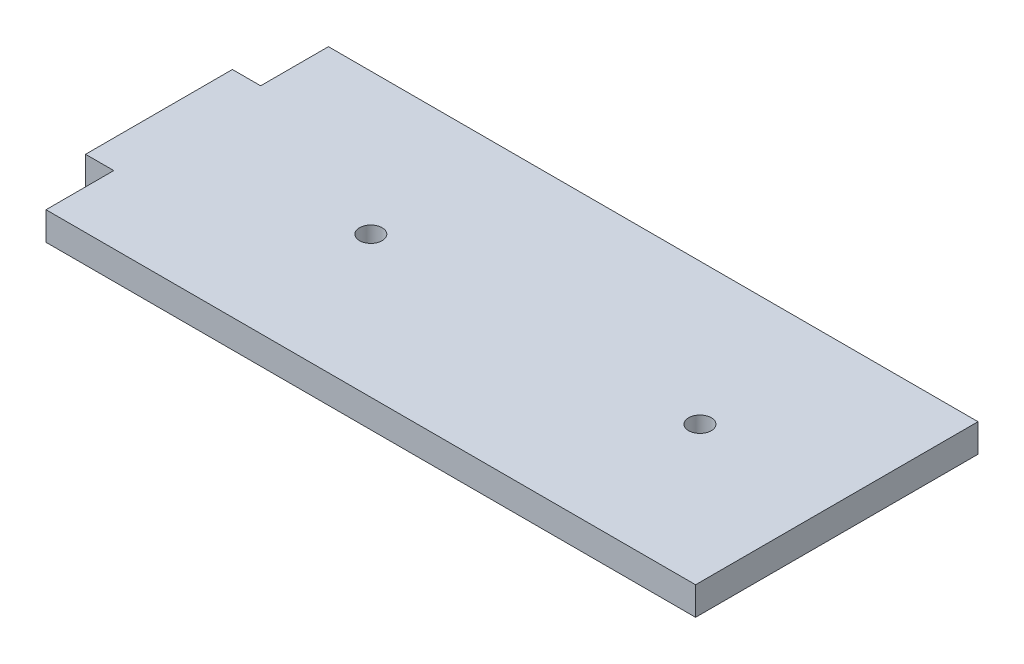
SolidWorks part; units mm, degrees
ref_plane "Front Plane" through (0, 0, 0) normal (0, 0, 1) x (1, 0, 0)
ref_plane "Top Plane" through (0, 0, 0) normal (0, 1, 0) x (1, 0, 0)
ref_plane "Right Plane" through (0, 0, 0) normal (1, 0, 0) x (0, 0, -1)
sketch "Sketch1" plane through (0, 0, 0) normal (0, 1, 0) x (1, 0, 0)
  line L1 (-38.1, 15.875) -> (38.1, 15.875)
  line L2 (-38.1, 15.875) -> (-38.1, -15.875)
  line L3 (-38.1, -15.875) -> (38.1, -15.875)
  line L4 (38.1, 15.875) -> (38.1, -15.875)
  line L5 (-38.1, 15.875) -> (38.1, -15.875) construction
  line L6 (-38.1, -15.875) -> (38.1, 15.875) construction
  point P0 (0, 0)
  dimension "D1" = 31.75
  dimension "D2" = 76.2
extrude "Boss-Extrude1" add sketch "Sketch1" along normal blind 3.175
sketch "Sketch2" plane through (0, 3.175, 0) normal (0, 1, 0) x (1, 0, 0)
  line L0 (-38.1, 15.875) -> (-38.1, -15.875) construction
  line L5 (38.1, 15.875) -> (-38.1, 15.875) construction
  line L7 (0, 0) -> (38.1, 0) construction
  line L8 (38.1, -15.875) -> (38.1, 15.875) construction
  line L10 (-34.925, 8.255) -> (-38.1, 8.255)
  line L11 (-34.925, 8.255) -> (-34.925, 15.875)
  line L12 (-34.925, 15.875) -> (-38.1, 15.875)
  line L13 (-38.1, 8.255) -> (-38.1, 15.875)
  line L14 (-34.925, -8.255) -> (-38.1, -8.255)
  line L15 (-34.925, -8.255) -> (-34.925, -15.875)
  line L16 (-34.925, -15.875) -> (-38.1, -15.875)
  line L17 (-38.1, -8.255) -> (-38.1, -15.875)
  circle A0 centre (-14.2803, 0) radius 1.27
  circle A1 centre (22.7197, 0) radius 1.27
  dimension "D1" = 37
  dimension "D3" = 3.175
extrude "Cut-Extrude1" cut sketch "Sketch2" against normal blind 3.175
